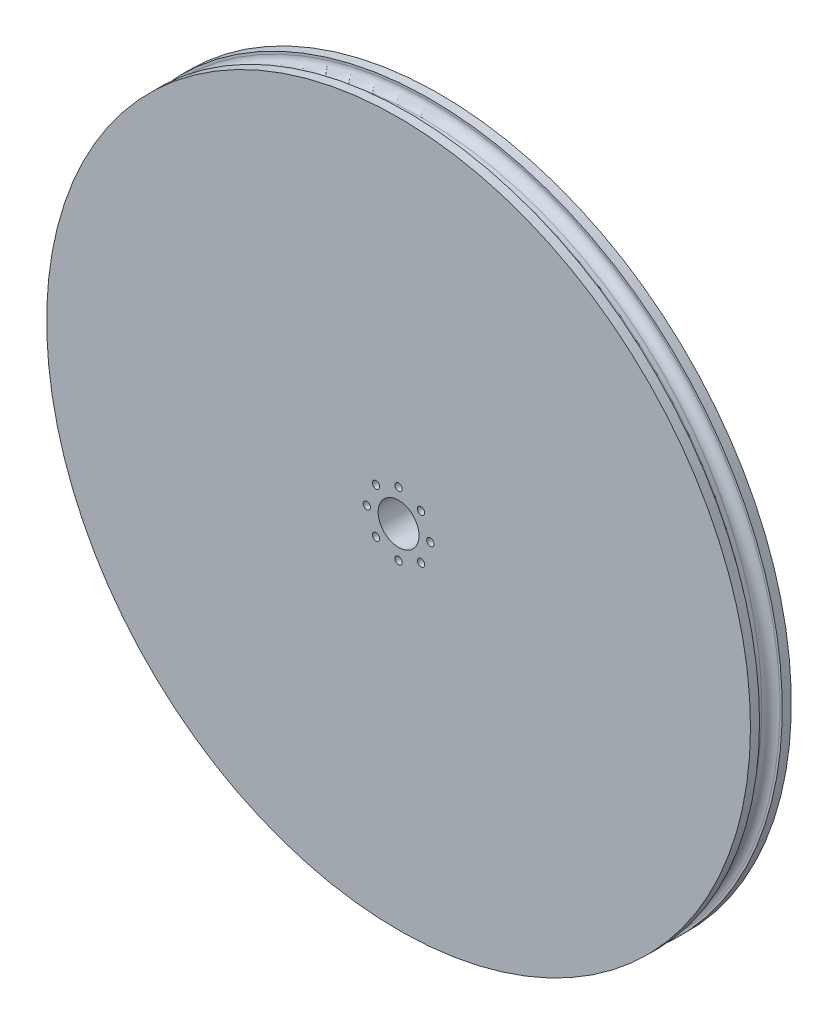
SolidWorks part; units mm, degrees
ref_plane "Front Plane" through (0, 0, 0) normal (0, 0, 1) x (1, 0, 0)
ref_plane "Top Plane" through (0, 0, 0) normal (0, 1, 0) x (1, 0, 0)
ref_plane "Right Plane" through (0, 0, 0) normal (1, 0, 0) x (0, 0, -1)
sketch "Sketch1" plane through (0, 0, 0) normal (0, 0, 1) x (1, 0, 0)
  circle A0 centre (0, 0) radius 75
  dimension "D1" = 150
extrude "Boss-Extrude1" add sketch "Sketch1" along normal blind 5
sketch "Sketch2" plane through (0, 0, 5) normal (0, 0, 1) x (1, 0, 0)
  circle A0 centre (0, 0) radius 77.5
extrude "Boss-Extrude2" add sketch "Sketch2" along normal blind 2
sketch "Sketch3" plane through (0, 0, 0) normal (0, 0, -1) x (-1, 0, 0)
  circle A1 centre (0, 0) radius 77.5 construction
  circle A3 centre (0, 0) radius 77.5
extrude "Boss-Extrude3" add sketch "Sketch3" along normal blind 2
sketch "Sketch5" plane through (0, 0, -2) normal (0, 0, -1) x (-1, 0, 0)
  arc A2 (-4.5, 0) -> (4.5, 0) centre (0, 0) ccw
  arc A3 (4.5, 0) -> (-4.5, 0) centre (0, 0) ccw
  arc A4 (-4.1497, 4.9497) -> (-5.7497, 4.9497) centre (-4.9497, 4.9497) ccw
  arc A5 (-5.7497, 4.9497) -> (-4.1497, 4.9497) centre (-4.9497, 4.9497) ccw
  arc A6 (-6.2, 0) -> (-7.8, 0) centre (-7, 0) ccw
  arc A7 (-7.8, 0) -> (-6.2, 0) centre (-7, 0) ccw
  arc A8 (-4.1497, -4.9497) -> (-5.7497, -4.9497) centre (-4.9497, -4.9497) ccw
  arc A9 (-5.7497, -4.9497) -> (-4.1497, -4.9497) centre (-4.9497, -4.9497) ccw
  arc A10 (-0.8, -7) -> (0.8, -7) centre (0, -7) ccw
  arc A11 (0.8, -7) -> (-0.8, -7) centre (0, -7) ccw
  arc A12 (4.1497, -4.9497) -> (5.7497, -4.9497) centre (4.9497, -4.9497) ccw
  arc A13 (5.7497, -4.9497) -> (4.1497, -4.9497) centre (4.9497, -4.9497) ccw
  arc A14 (6.2, 0) -> (7.8, 0) centre (7, 0) ccw
  arc A15 (7.8, 0) -> (6.2, 0) centre (7, 0) ccw
  arc A16 (4.1497, 4.9497) -> (5.7497, 4.9497) centre (4.9497, 4.9497) ccw
  arc A17 (5.7497, 4.9497) -> (4.1497, 4.9497) centre (4.9497, 4.9497) ccw
  arc A18 (0.8, 7) -> (-0.8, 7) centre (0, 7) ccw
  arc A19 (-0.8, 7) -> (0.8, 7) centre (0, 7) ccw
  point P0 (0, 0)
  point P3 (0, 0)
  point P44 (0, 0)
  point P45 (0, 0)
  point P46 (0, 0)
  point P47 (0, 0)
  point P48 (0, 0)
  point P49 (0, 0)
  point P50 (0, 0)
  point P51 (0, 0)
  point P52 (0, 0)
extrude "Cut-Extrude2" cut sketch "Sketch5" against normal through all
sketch "Sketch10" plane through (0, 0, -2) normal (0, 0, -1) x (-1, 0, 0)
  circle A0 centre (0, 0) radius 10
extrude "Cut-Extrude3" cut sketch "Sketch10" against normal blind 2.5
fillet "Fillet1" radius 2 2 edges at (75, 0, 0) (75, 0, 5)
